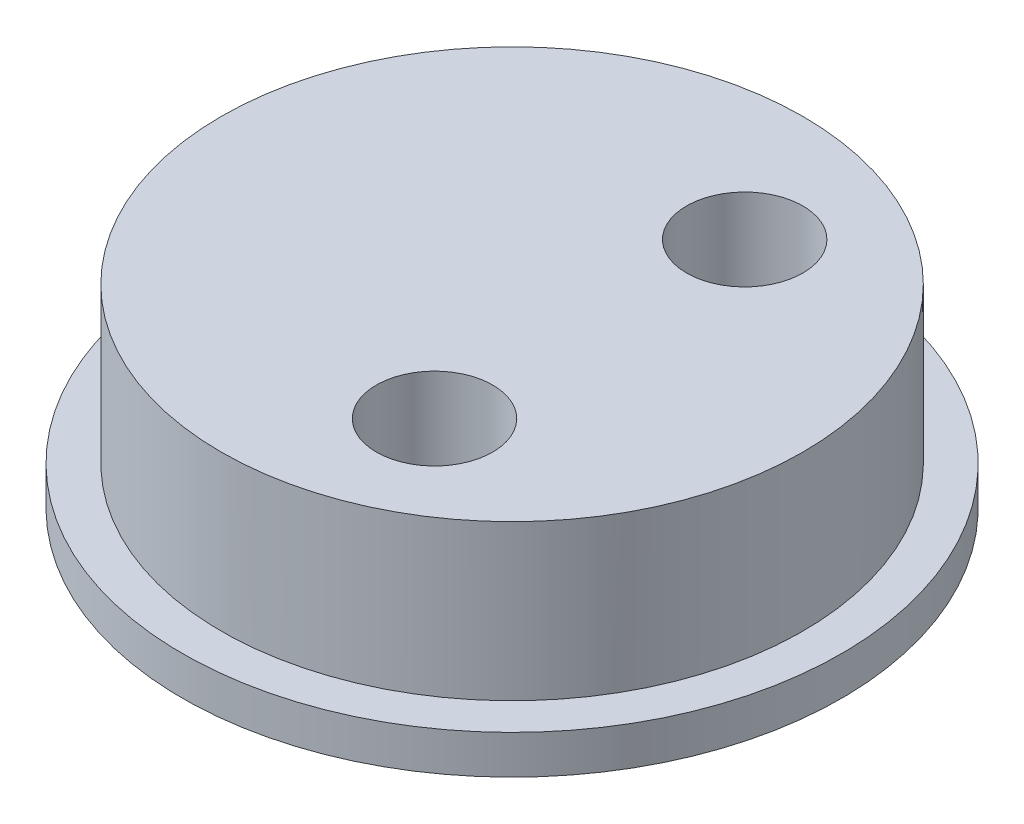
SolidWorks part; units mm, degrees
ref_plane "Front Plane" through (0, 0, 0) normal (0, 0, 1) x (1, 0, 0)
ref_plane "Top Plane" through (0, 0, 0) normal (0, 1, 0) x (1, 0, 0)
ref_plane "Right Plane" through (0, 0, 0) normal (1, 0, 0) x (0, 0, -1)
sketch "Sketch1" plane through (0, 0, 0) normal (0, 1, 0) x (1, 0, 0)
  line L0 (0, 0) -> (-2, 0) construction
  circle A1 centre (-2, 0) radius 7.5
  point P12 (0, 0)
  dimension "D3" = 15
  dimension "D2" = 2
extrude "Boss-Extrude1" add sketch "Sketch1" along normal blind 5
sketch "Sketch2" plane through (0, 0, 0) normal (0, -1, 0) x (1, 0, 0)
  line L0 (-12.8187, 0) -> (7.6603, 0) construction
  circle A0 centre (-2, 0) radius 8.5
  point P11 (0, 0)
  dimension "D2" = 17
  dimension "D1" = 2
extrude "Boss-Extrude2" add sketch "Sketch2" against normal blind 1
sketch "Sketch4" plane through (0, 5, 0) normal (0, 1, 0) x (1, 0, 0)
  line L0 (0, 8.8969) -> (0, -8.7328) construction
  circle A0 centre (0, 0) radius 4 construction
  circle A1 centre (0, 4) radius 1.5
  circle A2 centre (0, -4) radius 1.5
  dimension "D1" = 8
  dimension "D2" = 3
extrude "Cut-Extrude1" cut sketch "Sketch4" against normal through all
